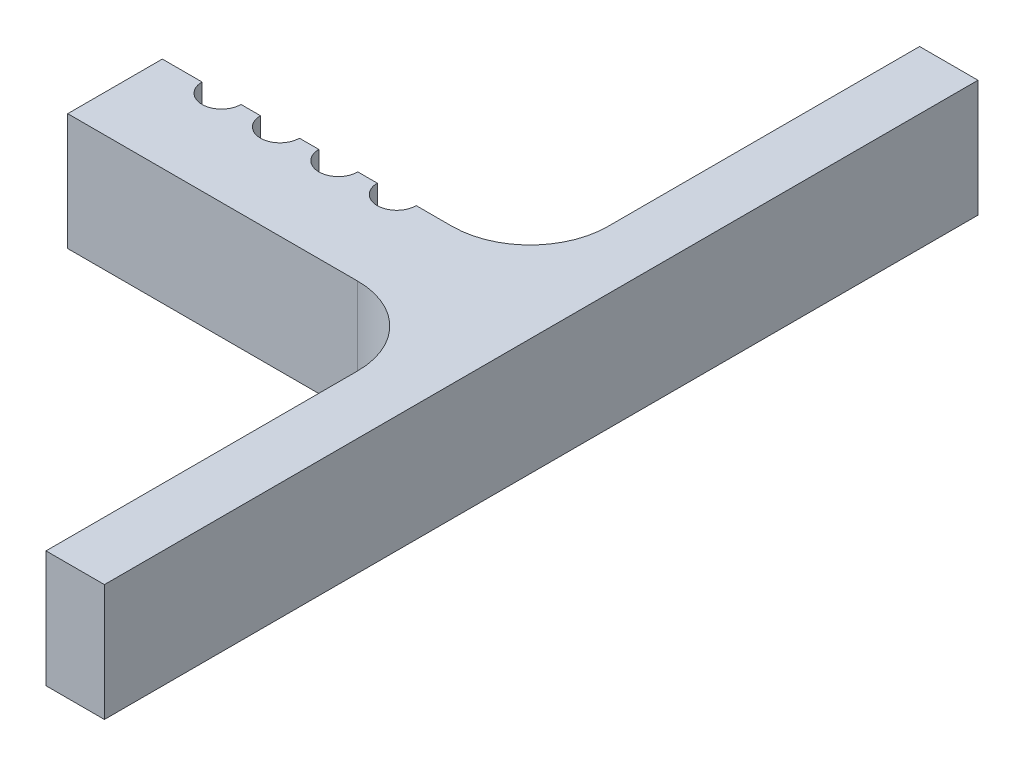
SolidWorks part; units mm, degrees
ref_plane "Front Plane" through (0, 0, 0) normal (0, 0, 1) x (1, 0, 0)
ref_plane "Top Plane" through (0, 0, 0) normal (0, 1, 0) x (1, 0, 0)
ref_plane "Right Plane" through (0, 0, 0) normal (1, 0, 0) x (0, 0, -1)
sketch "Sketch1" plane through (0, 0, 0) normal (0, 1, 0) x (1, 0, 0)
  line L5 (-46.8066, 10.2213) -> (-42.0853, 10.2213)
  line L6 (-42.0853, 10.2213) -> (-42.0853, 15.2213)
  line L7 (-42.0853, 10.2213) -> (-42.0853, 9.0065)
  line L8 (-46.8066, 10.2213) -> (-46.8066, 9.0065)
  line L9 (-46.8066, 9.0065) -> (-42.0853, 9.0065)
  line L10 (-42.0853, 15.2213) -> (-41.3353, 15.2213)
  line L11 (-42.0853, 9.0065) -> (-42.0853, 4.0065)
  line L12 (-42.0853, 4.0065) -> (-41.3353, 4.0065)
  line L13 (-41.3353, 4.0065) -> (-41.3353, 15.2213)
  line L14 (-42.0853, 10.2213) -> (-42.0853, 9.0065)
extrude "Boss-Extrude1" add sketch "Sketch1" along normal blind 1.5
fillet "Fillet1" radius 1 1 edges at (-42.0853, 0.75, -10.2213)
fillet "Fillet2" radius 1 1 edges at (-42.0853, 0.75, -9.0065)
sketch "Sketch2" plane through (0, 1.5, 0) normal (0, 1, 0) x (1, 0, 0)
  line L0 (-46.8066, 10.2213) -> (-46.0466, 10.2213)
  line L1 (-46.8066, 10.2213) -> (-43.0853, 10.2213) construction
  line L2 (-46.0466, 10.2213) -> (-44.9459, 10.2213)
  circle A0 centre (-46.0466, 10.2213) radius 0.25
  line M7 (-43.0853, 10.2213) -> (-46.8066, 10.2213)
extrude "Cut-Extrude1" cut sketch "Sketch2" against normal blind 2 contours A0 L2 M7
pattern_linear "LPattern1" count 4 spacing 0.75 along (1, 0, 0) of "Cut-Extrude1"
